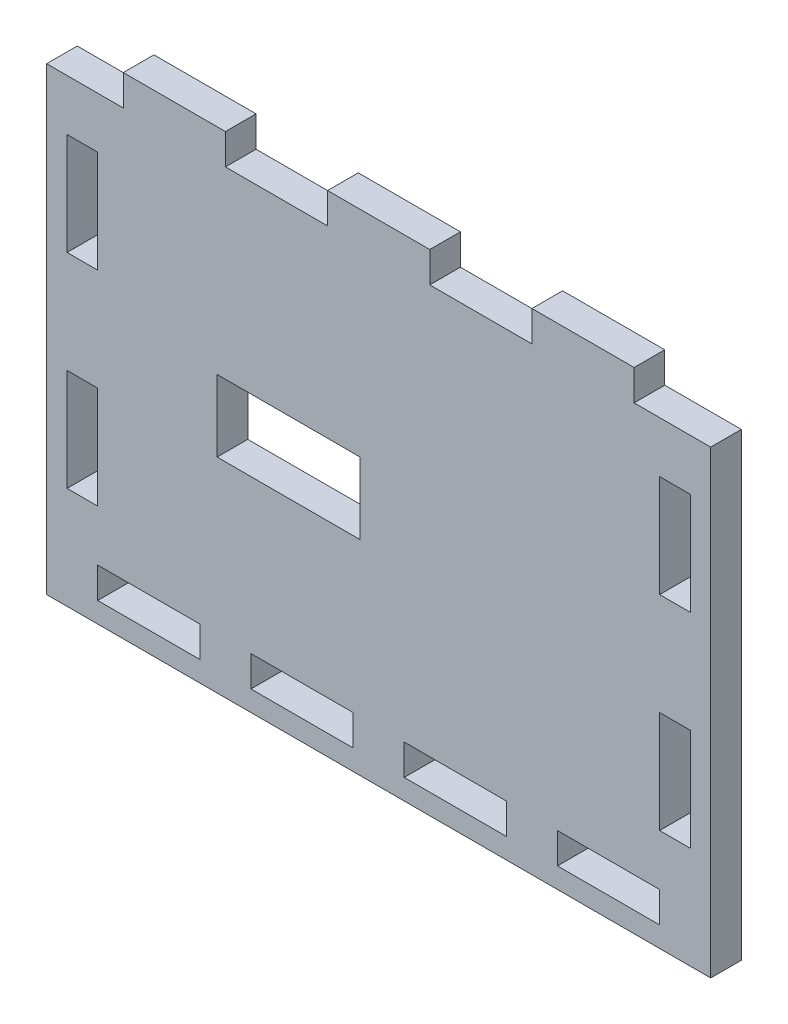
SolidWorks part; units mm, degrees
ref_plane "前视基准面" through (0, 0, 0) normal (0, 0, 1) x (1, 0, 0)
ref_plane "上视基准面" through (0, 0, 0) normal (0, 1, 0) x (1, 0, 0)
ref_plane "右视基准面" through (0, 0, 0) normal (1, 0, 0) x (0, 0, -1)
sketch "草图1" plane through (0, 0, 0) normal (0, 0, 1) x (1, 0, 0)
  line L0 (-5, 22.5) -> (-5, 25.5)
  line L1 (-32.5, 22.5) -> (-25, 22.5)
  line L2 (-32.5, 22.5) -> (-32.5, -22.5)
  line L3 (-32.5, -22.5) -> (32.5, -22.5)
  line L4 (32.5, 22.5) -> (32.5, -22.5)
  line L5 (-32.5, 22.5) -> (32.5, -22.5) construction
  line L6 (-32.5, -22.5) -> (32.5, 22.5) construction
  line L8 (-25, 22.5) -> (-25, 25.5)
  line L9 (-25, 25.5) -> (-15, 25.5)
  line L10 (-15, 22.5) -> (-15, 25.5)
  line L12 (5, 22.5) -> (5, 25.5)
  line L13 (-5, 25.5) -> (5, 25.5)
  line L14 (15, 22.5) -> (15, 25.5)
  line L16 (25, 22.5) -> (25, 25.5)
  line L17 (15, 25.5) -> (25, 25.5)
  line L18 (-12.5, -20.5) -> (-12.5, -17.5)
  line L19 (-27.5, -20.5) -> (-17.5, -20.5)
  line L20 (-27.5, -20.5) -> (-27.5, -17.5)
  line L21 (-27.5, -17.5) -> (-17.5, -17.5)
  line L22 (-17.5, -20.5) -> (-17.5, -17.5)
  line L23 (-12.5, -20.5) -> (-2.5, -20.5)
  line L24 (-2.5, -20.5) -> (-2.5, -17.5)
  line L25 (-12.5, -17.5) -> (-2.5, -17.5)
  line L26 (2.5, -20.5) -> (2.5, -17.5)
  line L27 (2.5, -20.5) -> (12.5, -20.5)
  line L28 (12.5, -20.5) -> (12.5, -17.5)
  line L29 (2.5, -17.5) -> (12.5, -17.5)
  line L30 (17.5, -20.5) -> (17.5, -17.5)
  line L31 (17.5, -20.5) -> (27.5, -20.5)
  line L32 (27.5, -20.5) -> (27.5, -17.5)
  line L33 (17.5, -17.5) -> (27.5, -17.5)
  line L39 (-30.5, -2.5) -> (-27.5, -2.5)
  line L40 (-27.5, -12.5) -> (-27.5, -2.5)
  line L41 (-30.5, -12.5) -> (-27.5, -12.5)
  line L42 (-30.5, -12.5) -> (-30.5, -2.5)
  line L52 (-15, 22.5) -> (-5, 22.5)
  line L53 (5, 22.5) -> (15, 22.5)
  line L54 (25, 22.5) -> (32.5, 22.5)
  line L55 (-30.5, 17.5) -> (-27.5, 17.5)
  line L56 (-27.5, 7.5) -> (-27.5, 17.5)
  line L57 (-30.5, 7.5) -> (-27.5, 7.5)
  line L58 (-30.5, 7.5) -> (-30.5, 17.5)
  line L59 (0, -55) -> (0, 55) construction
  line L60 (30.5, -12.5) -> (30.5, -2.5)
  line L61 (30.5, -12.5) -> (27.5, -12.5)
  line L62 (27.5, -12.5) -> (27.5, -2.5)
  line L63 (30.5, -2.5) -> (27.5, -2.5)
  line L64 (30.5, 7.5) -> (30.5, 17.5)
  line L65 (30.5, 7.5) -> (27.5, 7.5)
  line L66 (27.5, 7.5) -> (27.5, 17.5)
  line L67 (30.5, 17.5) -> (27.5, 17.5)
  point P0 (0, 0)
  dimension "D1" = 65
  dimension "D2" = 45
  dimension "D3" = 10
  dimension "D4" = 3
  dimension "D5" = 7.5
  dimension "D7" = 10
  dimension "D8" = 3
  dimension "D9" = 2
  dimension "D10" = 5
  dimension "D12" = 10
  dimension "D13" = 3
  dimension "D14" = 10
  dimension "D15" = 2
  dimension "D6" = 3
  dimension "D11" = 4
extrude "凸台-拉伸1" add sketch "草图1" along normal blind 3
sketch "草图2" plane through (0, 0, 3) normal (0, 0, 1) x (1, 0, 0)
  line L0 (-2.5, -17.5) -> (-12.5, -17.5) construction
  line L1 (-15.8127, -2.5) -> (-1.8127, -2.5)
  line L2 (-15.8127, -2.5) -> (-15.8127, 4.5)
  line L3 (-15.8127, 4.5) -> (-1.8127, 4.5)
  line L4 (-1.8127, -2.5) -> (-1.8127, 4.5)
  dimension "D1" = 14
  dimension "D2" = 7
  dimension "D3" = 15
extrude "切除-拉伸1" cut sketch "草图2" against normal blind 10
